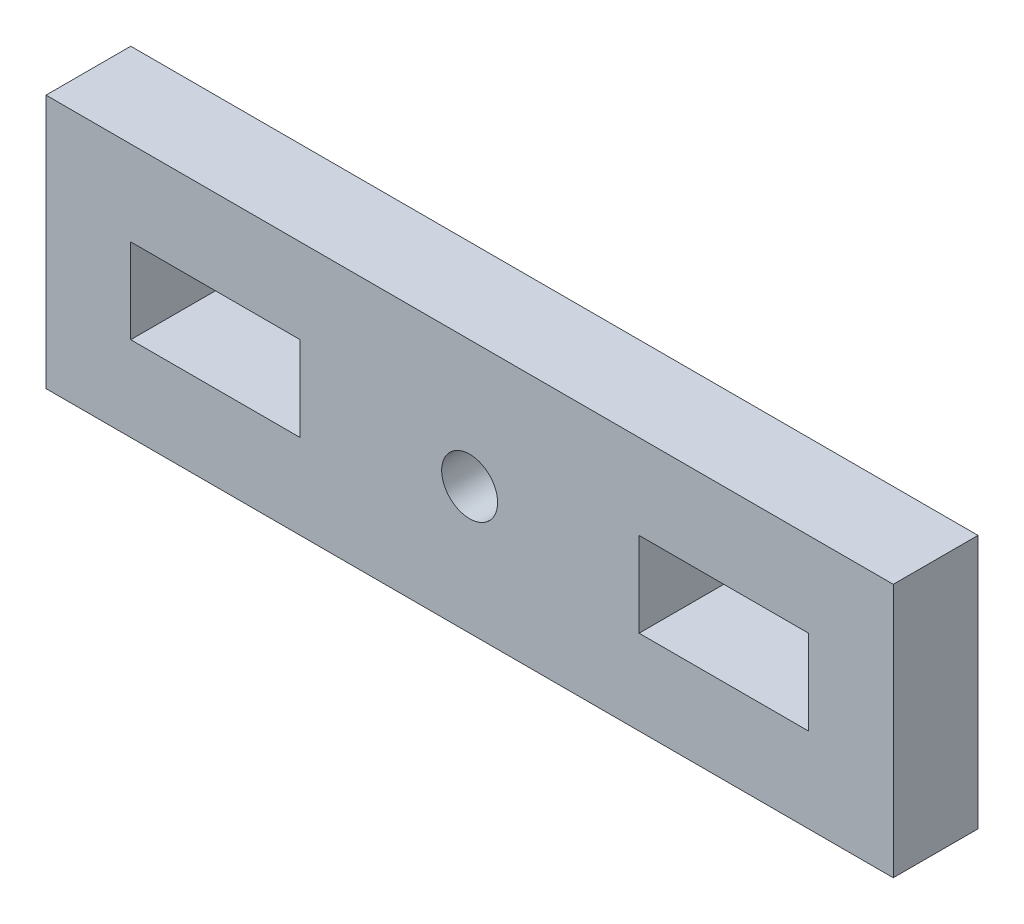
SolidWorks part; units mm, degrees
ref_plane "Front Plane" through (0, 0, 0) normal (0, 0, 1) x (1, 0, 0)
ref_plane "Top Plane" through (0, 0, 0) normal (0, 1, 0) x (1, 0, 0)
ref_plane "Right Plane" through (0, 0, 0) normal (1, 0, 0) x (0, 0, -1)
sketch "Sketch1" plane through (0, 0, 0) normal (0, 0, 1) x (1, 0, 0)
  line L1 (-31.75, -9.525) -> (31.75, -9.525)
  line L2 (-31.75, -9.525) -> (-31.75, 9.525)
  line L3 (-31.75, 9.525) -> (31.75, 9.525)
  line L4 (31.75, -9.525) -> (31.75, 9.525)
  line L5 (-31.75, -9.525) -> (31.75, 9.525) construction
  line L6 (-31.75, 9.525) -> (31.75, -9.525) construction
  point P0 (0, 0)
  dimension "D1" = 19.05
  dimension "D2" = 63.5
extrude "Boss-Extrude1" add sketch "Sketch1" along normal blind 6.35
sketch "Sketch2" plane through (0, 0, 6.35) normal (0, 0, 1) x (1, 0, 0)
  line L0 (0, 3.175) -> (0, -3.175) construction
  line L1 (-31.75, -9.525) -> (31.75, -9.525) construction
  line L2 (-31.75, -3.175) -> (31.75, -3.175) construction
  line L3 (-31.75, 9.525) -> (-31.75, -9.525) construction
  line L4 (31.75, -9.525) -> (31.75, 9.525) construction
  line L5 (-31.75, 3.175) -> (31.75, 3.175) construction
  line L7 (-25.4, 3.175) -> (-12.7, 3.175)
  line L8 (-25.4, 3.175) -> (-25.4, -3.175)
  line L9 (-25.4, -3.175) -> (-12.7, -3.175)
  line L10 (-12.7, 3.175) -> (-12.7, -3.175)
  line L11 (12.7, 3.175) -> (25.4, 3.175)
  line L12 (12.7, 3.175) -> (12.7, -3.175)
  line L13 (12.7, -3.175) -> (25.4, -3.175)
  line L14 (25.4, 3.175) -> (25.4, -3.175)
  circle A0 centre (0, 0) radius 2.0955
  dimension "D3" = 4.191
  dimension "D1" = 6.35
  dimension "D2" = 6.35
  dimension "D4" = 12.7
  dimension "D5" = 12.7
  dimension "D6" = 12.7
  dimension "D7" = 12.7
extrude "Cut-Extrude1" cut sketch "Sketch2" against normal blind 6.35
